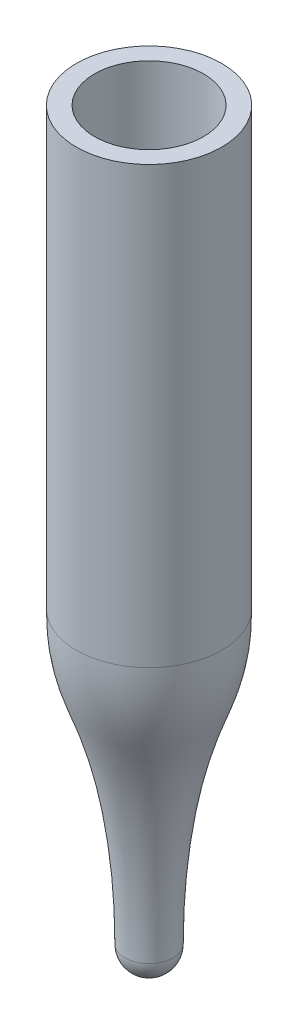
SolidWorks part; units mm, degrees
material "Acrylique (impact moyen-haut)"
ref_plane "Plan de face" through (0, 0, 0) normal (0, 0, 1) x (1, 0, 0)
ref_plane "Plan de dessus" through (0, 0, 0) normal (0, 1, 0) x (1, 0, 0)
ref_plane "Plan de droite" through (0, 0, 0) normal (1, 0, 0) x (0, 0, -1)
sketch "Esquisse1" plane through (0, 0, 0) normal (0, 0, 1) x (1, 0, 0)
  line L0 (0, 0) -> (0, 31) construction
  line L1 (3, 31) -> (3, 13)
  line L2 (1, -2.3896) -> (1, 4.3909) construction
  line L3 (3, 10.0667) -> (3, 17.2914) construction
  line L4 (2.25, 31) -> (2.25, 13)
  line L5 (2.25, 31) -> (3, 31)
  line L6 (0, 0.75) -> (0, 0)
  arc A0 (0, 0) -> (1, 1) centre (0, 1) ccw
  arc A1 (0, 0.75) -> (0.25, 1) centre (0, 1) ccw
  spline S0 degree 3 poles (3, 13) (3, 10.8288) (1.9097, 9.139) (1, 4.3126) (1, 1) knots 0 0 0 0 0.477481 1 1 1 1
  spline S1 degree 1 poles (2.25, 13) (0.25, 1) knots 0 0 1 1 construction
  spline S2 degree 3 poles (2.25, 13) (2.25, 12.8717) (2.2458, 12.607) (2.222, 12.1439) (2.1665, 11.6319) (2.0665, 11.1056) (1.8955, 10.4656) (1.6144, 9.6914) (1.2088, 8.5464) (0.8334, 7.0907) (0.5209, 5.3572) (0.3415, 3.6719) (0.2639, 2.197) (0.25, 1.3936) (0.25, 1) knots 0 0 0 0 0.03125 0.0625 0.125 0.1875 0.25 0.375 0.5 0.625 0.75 0.875 0.9375 1 1 1 1
  dimension "D4" = 1
  dimension "D1" = 31
  dimension "D2" = 18
  dimension "D3" = 3
  dimension "D5" = 2
  dimension "D6" = 8.5
  dimension "D7" = 0.75
revolve "Révolution1" add sketch "Esquisse1" angle 360 about L0
